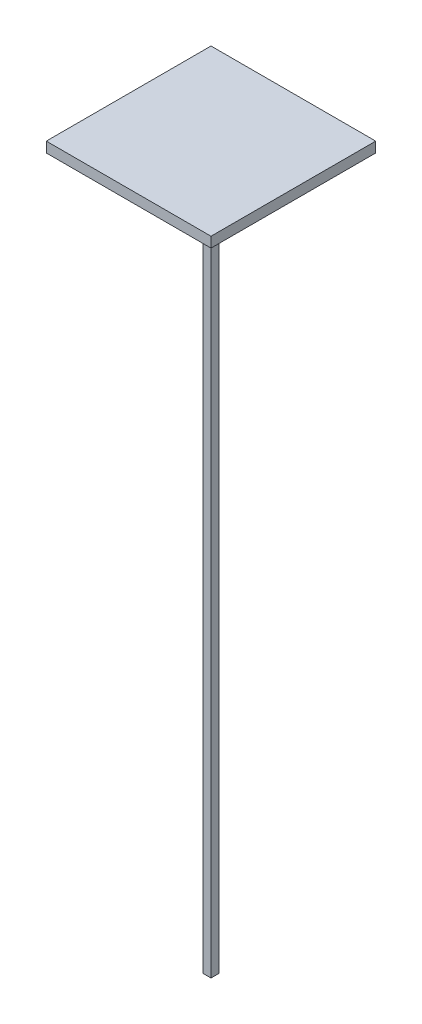
SolidWorks part; units mm, degrees
ref_plane "Plan de face" through (0, 0, 0) normal (0, 0, 1) x (1, 0, 0)
ref_plane "Plan de dessus" through (0, 0, 0) normal (0, 1, 0) x (1, 0, 0)
ref_plane "Plan de droite" through (0, 0, 0) normal (1, 0, 0) x (0, 0, -1)
sketch "Esquisse1" plane through (0, 0, 0) normal (0, 1, 0) x (1, 0, 0)
  line L1 (0, 0) -> (4, 0)
  line L2 (0, 0) -> (0, 4)
  line L3 (0, 4) -> (4, 4)
  line L4 (4, 0) -> (4, 4)
  dimension "D1" = 4
  dimension "D2" = 4
extrude "Extrusion1" add sketch "Esquisse1" along normal blind 345
sketch "Esquisse2" plane through (0, 345, 0) normal (0, 1, 0) x (1, 0, 0)
  line L0 (-38, 42) -> (42, -38) construction
  line L1 (-38, 42) -> (42, 42)
  line L2 (-38, 42) -> (-38, -38)
  line L3 (-38, -38) -> (42, -38)
  line L4 (42, 42) -> (42, -38)
  line L5 (42, 42) -> (-38, -38) construction
  line L6 (2, 4) -> (2, 0) construction
  line L7 (4, 4) -> (0, 4) construction
  line L8 (0, 0) -> (4, 0) construction
  point P10 (2, 2)
  dimension "D1" = 80
extrude "Extrusion2" add sketch "Esquisse2" along normal blind 5
